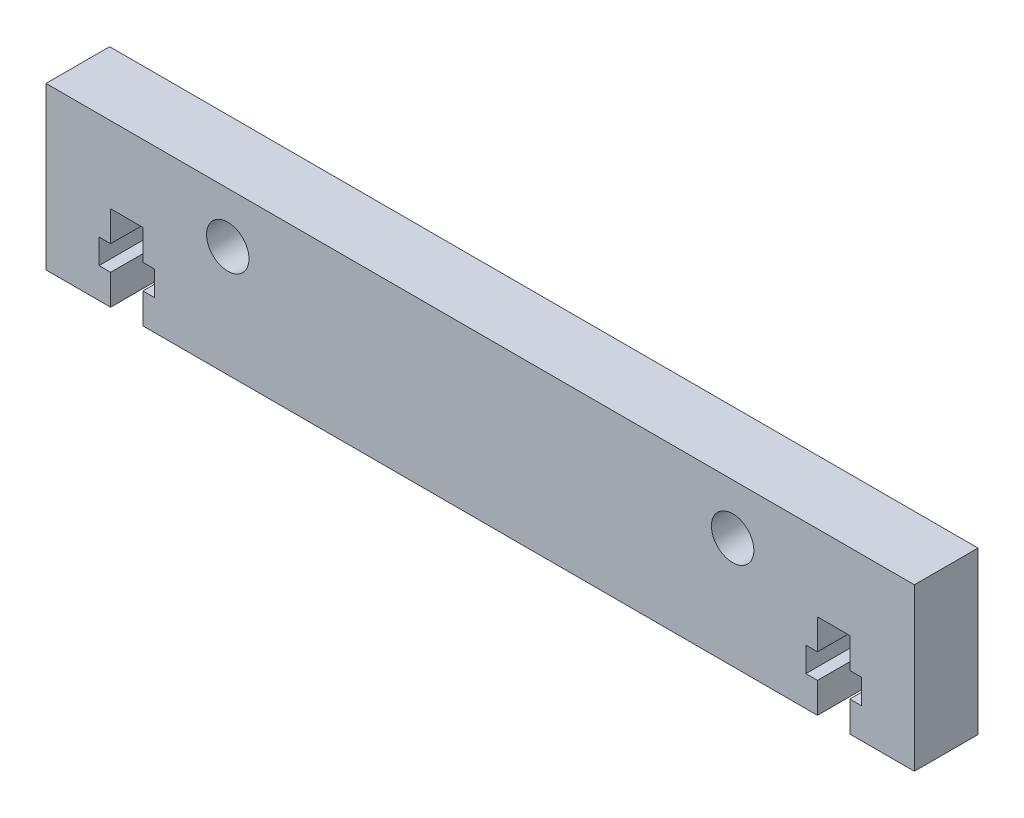
SolidWorks part; units mm, degrees
ref_plane "Front Plane" through (0, 0, 0) normal (0, 0, 1) x (1, 0, 0)
ref_plane "Top Plane" through (0, 0, 0) normal (0, 1, 0) x (1, 0, 0)
ref_plane "Right Plane" through (0, 0, 0) normal (1, 0, 0) x (0, 0, -1)
sketch "Sketch1" plane through (0, 0, 0) normal (0, 0, 1) x (1, 0, 0)
  line L0 (0, 0) -> (0, 37.2298) construction
  line L1 (33.4, 0) -> (-33.4, 0)
  line L2 (-33.4, 0) -> (-33.4, 3)
  line L3 (-33.4, 3) -> (-32.25, 3)
  line L4 (-32.25, 3) -> (-32.25, 5.45)
  line L5 (-32.25, 5.45) -> (-33.4, 5.45)
  line L6 (-33.4, 5.45) -> (-33.4, 8.45)
  line L7 (-33.4, 8.45) -> (-36.6, 8.45)
  line L8 (-36.6, 8.45) -> (-36.6, 5.45)
  line L9 (-36.6, 5.45) -> (-37.75, 5.45)
  line L10 (-37.75, 5.45) -> (-37.75, 3)
  line L11 (-37.75, 3) -> (-36.6, 3)
  line L12 (-36.6, 3) -> (-36.6, 0)
  line L13 (-36.6, 0) -> (-43, 0)
  line L14 (-43, 0) -> (-43, 16)
  line L15 (-43, 16) -> (43, 16)
  line L16 (-35, 8.45) -> (-35, 0) construction
  line L17 (43, 0) -> (43, 16)
  line L18 (36.6, 0) -> (43, 0)
  line L19 (36.6, 3) -> (36.6, 0)
  line L20 (37.75, 3) -> (36.6, 3)
  line L21 (37.75, 5.45) -> (37.75, 3)
  line L22 (36.6, 5.45) -> (37.75, 5.45)
  line L23 (36.6, 8.45) -> (36.6, 5.45)
  line L24 (33.4, 8.45) -> (36.6, 8.45)
  line L25 (33.4, 5.45) -> (33.4, 8.45)
  line L26 (32.25, 5.45) -> (33.4, 5.45)
  line L27 (33.4, 0) -> (33.4, 3)
  line L28 (33.4, 3) -> (32.25, 3)
  line L29 (32.25, 3) -> (32.25, 5.45)
  circle A0 centre (-25, 11) radius 2.1
  circle A1 centre (25, 11) radius 2.1
  point P24 (-55.9224, -2.5624)
  point P28 (0, 16)
  point P39 (0, 0)
  dimension "D1" = 4.2
  dimension "D2" = 25
  dimension "D3" = 3
  dimension "D4" = 3
  dimension "D5" = 2.45
  dimension "D6" = 3.2
  dimension "D7" = 35
  dimension "D8" = 11
  dimension "D9" = 5.5
  dimension "D10" = 43
  dimension "D11" = 5
extrude "Boss-Extrude1" add sketch "Sketch1" along normal blind 6.3
